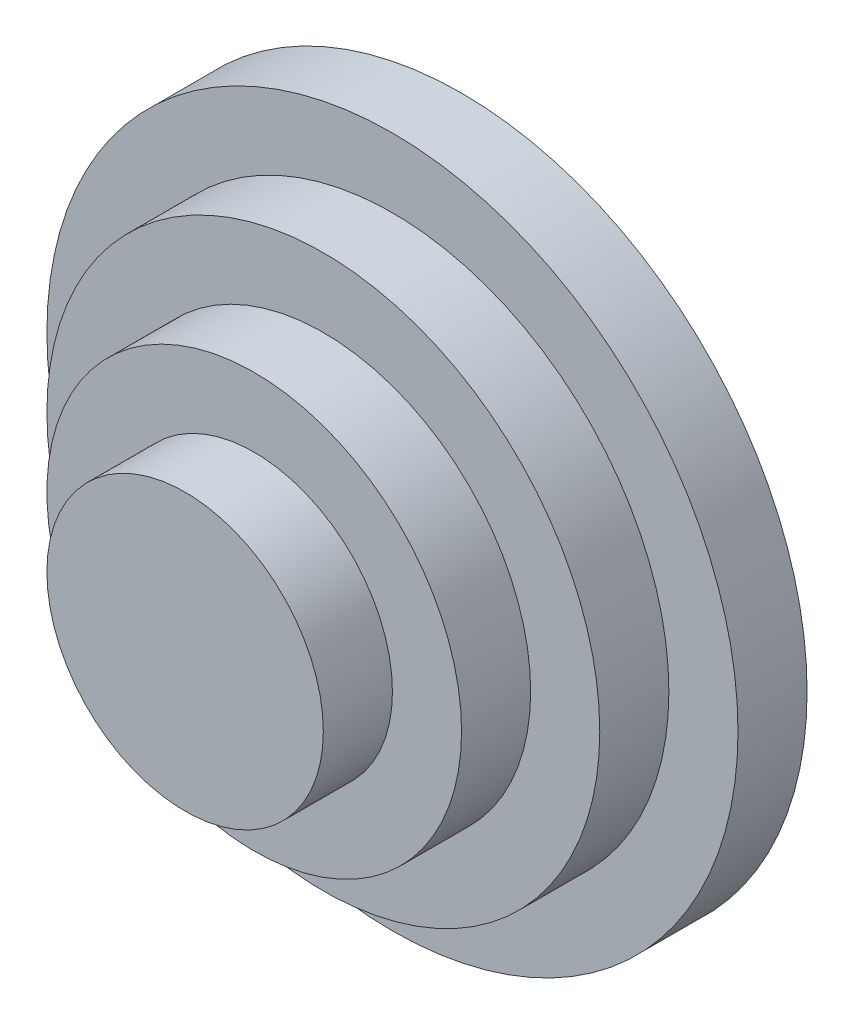
SolidWorks part; units mm, degrees
material "Сталь"
ref_plane "Спереди" through (0, 0, 0) normal (0, 0, 1) x (1, 0, 0)
ref_plane "Сверху" through (0, 0, 0) normal (0, 1, 0) x (1, 0, 0)
ref_plane "Справа" through (0, 0, 0) normal (1, 0, 0) x (0, 0, -1)
sketch "Эскиз1" plane through (0, 0, 0) normal (0, 0, 1) x (1, 0, 0)
  circle A0 centre (0, 0) radius 25
  dimension "D1" = 50
extrude "Бобышка-Вытянуть1" add sketch "Эскиз1" along normal blind 5
sketch "Эскиз2" plane through (0, 0, 5) normal (0, 0, 1) x (1, 0, 0)
  circle A3 centre (0, 0) radius 20
  circle A4 centre (0, 0) radius 20
  dimension "D1" = 5
extrude "Бобышка-Вытянуть2" add sketch "Эскиз2" along normal blind 5
sketch "Эскиз3" plane through (0, 0, 10) normal (0, 0, 1) x (1, 0, 0)
  circle A2 centre (0, 0) radius 15
  circle A3 centre (0, 0) radius 15
  dimension "D1" = 5
extrude "Бобышка-Вытянуть3" add sketch "Эскиз3" along normal blind 5
sketch "Эскиз4" plane through (0, 0, 15) normal (0, 0, 1) x (1, 0, 0)
  circle A2 centre (0, 0) radius 10
  circle A3 centre (0, 0) radius 10
  dimension "D1" = 5
extrude "Бобышка-Вытянуть4" add sketch "Эскиз4" along normal blind 5
